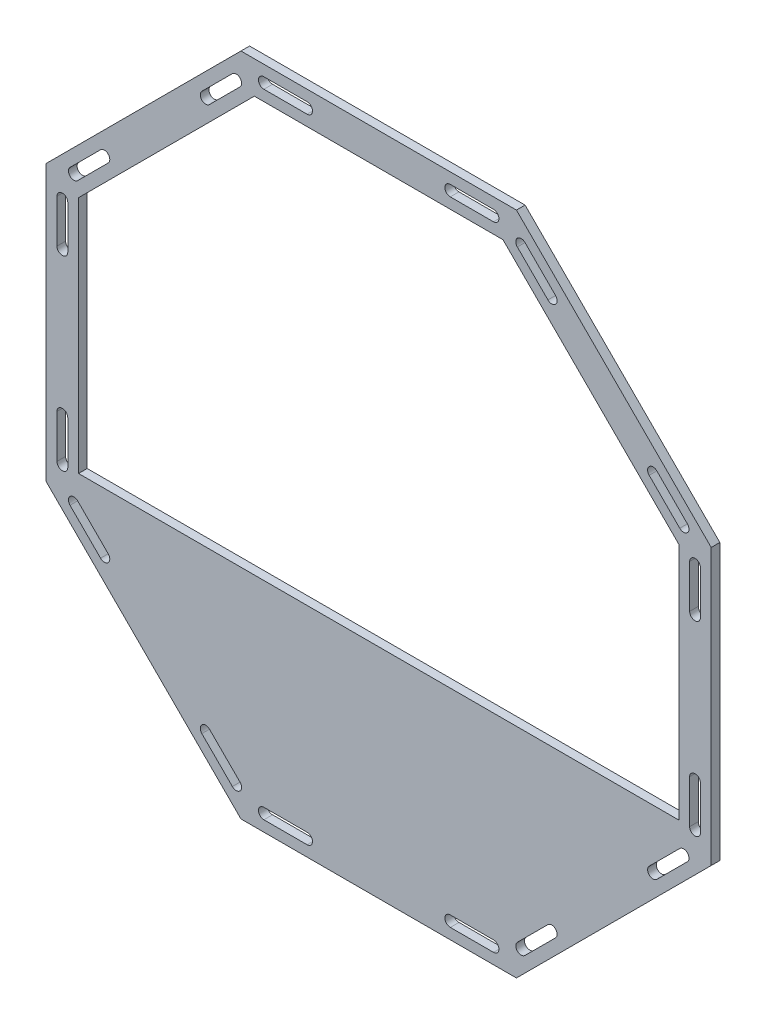
SolidWorks part; units mm, degrees
ref_plane "Front Plane" through (0, 0, 0) normal (0, 0, 1) x (1, 0, 0)
ref_plane "Top Plane" through (0, 0, 0) normal (0, 1, 0) x (1, 0, 0)
ref_plane "Right Plane" through (0, 0, 0) normal (1, 0, 0) x (0, 0, -1)
sketch "Sketch1" plane through (0, 0, 0) normal (0, 0, 1) x (1, 0, 0)
  line L1 (307.8122, -127.5) -> (307.8122, 127.5)
  line L2 (307.8122, 127.5) -> (127.5, 307.8122)
  line L3 (127.5, 307.8122) -> (-127.5, 307.8122)
  line L4 (-127.5, 307.8122) -> (-307.8122, 127.5)
  line L5 (-307.8122, 127.5) -> (-307.8122, -127.5)
  line L6 (-307.8122, -127.5) -> (-127.5, -307.8122)
  line L7 (-127.5, -307.8122) -> (127.5, -307.8122)
  line L8 (127.5, -307.8122) -> (307.8122, -127.5)
  circle A1 centre (0, 0) radius 333.1736 construction
  dimension "D1" = 255
extrude "Boss-Extrude1" add sketch "Sketch1" along normal blind 8
sketch "Sketch2" plane through (0, 0, 0) normal (0, 0, -1) x (-1, 0, 0)
  line L0 (-247.7082, 159.3198) -> (-261.8503, 173.4619)
  line L1 (-247.7082, 159.3198) -> (-159.3198, 247.7082)
  line L2 (-261.8503, 173.4619) -> (-173.4619, 261.8503)
  line L3 (-159.3198, 247.7082) -> (-173.4619, 261.8503)
  line L4 (-307.8122, 127.5) -> (-127.5, 307.8122) construction
  line L6 (-217.6561, 217.6561) -> (-147.1936, 147.1936) construction
  dimension "D1" = 20
  dimension "D2" = 125
  dimension "D3" = 62.5
sketch "Esquisse2" plane through (0, 0, 8) normal (0, 0, 1) x (1, 0, 0)
  line L0 (-277.8122, 115.0736) -> (-277.8122, -106.0285)
  line L1 (-127.5, 307.8122) -> (-307.8122, 127.5) construction
  line L2 (-307.8122, 127.5) -> (-307.8122, -127.5) construction
  line L5 (-115.0736, 277.8122) -> (-277.8122, 115.0736)
  line L13 (115.0736, 277.8122) -> (-115.0736, 277.8122)
  line L14 (-277.8122, -106.0285) -> (277.8122, -106.0285)
  line L25 (127.5, 307.8122) -> (-127.5, 307.8122) construction
  line L26 (0, 0) -> (0, 307.8122) construction
  line L30 (115.0736, 277.8122) -> (277.8122, 115.0736)
  line L31 (277.8122, 115.0736) -> (277.8122, -106.0285)
  dimension "D1" = 30
  dimension "D2" = 30
  dimension "D5" = 30
extrude "Enlèv. mat.-Extru.2" cut sketch "Esquisse2" against normal blind 10
sketch "Esquisse3" plane through (0, 0, 8) normal (0, 0, 1) x (1, 0, 0)
  line L0 (-282.1898, 131.8558) -> (-253.9055, 160.1401) construction
  line L3 (-285.7253, 135.3914) -> (-257.4411, 163.6757)
  line L4 (-278.6543, 128.3203) -> (-250.37, 156.6046)
  line L7 (-207.0337, 207.012) -> (-173.512, 173.4902) construction
  line L8 (-131.8776, 282.1681) -> (-160.1619, 253.8838) construction
  line L9 (-135.4131, 285.7036) -> (-163.6974, 257.4193)
  line L10 (-128.342, 278.6325) -> (-156.6263, 250.3483)
  line L13 (0.0158, 292.7747) -> (0.0158, -292.8498) construction
  line L16 (-292.7964, -0.0376) -> (292.828, -0.0376) construction
  line L17 (-121.271, 292.7747) -> (121.3026, -292.8498) construction
  line L20 (-106.271, 292.7747) -> (-66.271, 292.7747) construction
  line L23 (-106.271, 297.7747) -> (-66.271, 297.7747)
  line L24 (-106.271, 287.7747) -> (-66.271, 287.7747)
  line L25 (106.3026, 292.7747) -> (66.3026, 292.7747) construction
  line L28 (106.3026, 297.7747) -> (66.3026, 297.7747)
  line L31 (106.3026, 287.7747) -> (66.3026, 287.7747)
  line L34 (-292.7964, 121.2492) -> (292.828, -121.3243) construction
  line L37 (-292.7964, 106.2492) -> (-292.7964, 66.2492) construction
  line L40 (-297.7964, 106.2492) -> (-297.7964, 66.2492)
  line L43 (-287.7964, 106.2492) -> (-287.7964, 66.2492)
  line L46 (-292.7964, -106.3243) -> (-292.7964, -66.3243) construction
  line L49 (-297.7964, -106.3243) -> (-297.7964, -66.3243)
  line L50 (-287.7964, -106.3243) -> (-287.7964, -66.3243)
  line L53 (131.9092, 282.1681) -> (160.1935, 253.8838) construction
  line L56 (-292.7964, -121.3243) -> (292.828, 121.2492) construction
  line L57 (282.2214, -131.9309) -> (253.9372, -160.2152) construction
  line L58 (285.757, -135.4665) -> (257.4727, -163.7508)
  line L59 (278.6859, -128.3954) -> (250.4016, -156.6797)
  line L60 (131.9092, -282.2432) -> (160.1935, -253.9589) construction
  line L61 (135.4447, -285.7787) -> (163.729, -257.4944)
  line L62 (128.3737, -278.7076) -> (156.658, -250.4234)
  line L63 (106.3026, -292.8498) -> (66.3026, -292.8498) construction
  line L64 (106.3026, -297.8498) -> (66.3026, -297.8498)
  line L65 (106.3026, -287.8498) -> (66.3026, -287.8498)
  line L66 (-106.271, -292.8498) -> (-66.271, -292.8498) construction
  line L67 (-106.271, -297.8498) -> (-66.271, -297.8498)
  line L68 (-106.271, -287.8498) -> (-66.271, -287.8498)
  line L69 (-131.8776, -282.2432) -> (-160.1619, -253.9589) construction
  line L70 (-135.4131, -285.7787) -> (-163.6974, -257.4944)
  line L71 (-128.342, -278.7076) -> (-156.6263, -250.4234)
  line L72 (-282.1898, -131.9309) -> (-253.9055, -160.2152) construction
  line L73 (-285.7253, -135.4665) -> (-257.4411, -163.7508)
  line L74 (-278.6543, -128.3954) -> (-250.37, -156.6797)
  line L75 (292.828, -106.3243) -> (292.828, -66.3243) construction
  line L76 (297.828, -106.3243) -> (297.828, -66.3243)
  line L77 (287.828, -106.3243) -> (287.828, -66.3243)
  line L78 (292.828, 106.2492) -> (292.828, 66.2492) construction
  line L79 (297.828, 106.2492) -> (297.828, 66.2492)
  line L80 (287.828, 106.2492) -> (287.828, 66.2492)
  line L81 (127.5158, 307.7747) -> (-127.4842, -307.8498) construction
  line L82 (135.4447, 285.7036) -> (163.729, 257.4193)
  line L83 (128.3737, 278.6325) -> (156.658, 250.3483)
  line L84 (282.2214, 131.8558) -> (253.9372, 160.1401) construction
  line L85 (285.757, 135.3914) -> (257.4727, 163.6757)
  line L86 (278.6859, 128.3203) -> (250.4016, 156.6046)
  arc A32 (135.4447, 285.7036) -> (128.3737, 278.6325) centre (131.9092, 282.1681) ccw
  arc A33 (-285.7253, 135.3914) -> (-278.6543, 128.3203) centre (-282.1898, 131.8558) ccw
  arc A34 (-250.37, 156.6046) -> (-257.4411, 163.6757) centre (-253.9055, 160.1401) ccw
  arc A35 (-135.4131, 285.7036) -> (-128.342, 278.6325) centre (-131.8776, 282.1681) cw
  arc A36 (-156.6263, 250.3483) -> (-163.6974, 257.4193) centre (-160.1619, 253.8838) cw
  arc A37 (-106.271, 297.7747) -> (-106.271, 287.7747) centre (-106.271, 292.7747) ccw
  arc A38 (-66.271, 287.7747) -> (-66.271, 297.7747) centre (-66.271, 292.7747) ccw
  arc A39 (106.3026, 297.7747) -> (106.3026, 287.7747) centre (106.3026, 292.7747) cw
  arc A40 (66.3026, 287.7747) -> (66.3026, 297.7747) centre (66.3026, 292.7747) cw
  arc A41 (-297.7964, 106.2492) -> (-287.7964, 106.2492) centre (-292.7964, 106.2492) cw
  arc A42 (-287.7964, 66.2492) -> (-297.7964, 66.2492) centre (-292.7964, 66.2492) cw
  arc A43 (-297.7964, -106.3243) -> (-287.7964, -106.3243) centre (-292.7964, -106.3243) ccw
  arc A44 (-287.7964, -66.3243) -> (-297.7964, -66.3243) centre (-292.7964, -66.3243) ccw
  arc A45 (285.757, -135.4665) -> (278.6859, -128.3954) centre (282.2214, -131.9309) ccw
  arc A46 (250.4016, -156.6797) -> (257.4727, -163.7508) centre (253.9372, -160.2152) ccw
  arc A47 (135.4447, -285.7787) -> (128.3737, -278.7076) centre (131.9092, -282.2432) cw
  arc A48 (156.658, -250.4234) -> (163.729, -257.4944) centre (160.1935, -253.9589) cw
  arc A49 (106.3026, -297.8498) -> (106.3026, -287.8498) centre (106.3026, -292.8498) ccw
  arc A50 (66.3026, -287.8498) -> (66.3026, -297.8498) centre (66.3026, -292.8498) ccw
  arc A51 (-106.271, -297.8498) -> (-106.271, -287.8498) centre (-106.271, -292.8498) cw
  arc A52 (-66.271, -287.8498) -> (-66.271, -297.8498) centre (-66.271, -292.8498) cw
  arc A53 (-135.4131, -285.7787) -> (-128.342, -278.7076) centre (-131.8776, -282.2432) ccw
  arc A54 (-156.6263, -250.4234) -> (-163.6974, -257.4944) centre (-160.1619, -253.9589) ccw
  arc A55 (-285.7253, -135.4665) -> (-278.6543, -128.3954) centre (-282.1898, -131.9309) cw
  arc A56 (-250.37, -156.6797) -> (-257.4411, -163.7508) centre (-253.9055, -160.2152) cw
  arc A57 (297.828, -106.3243) -> (287.828, -106.3243) centre (292.828, -106.3243) cw
  arc A58 (287.828, -66.3243) -> (297.828, -66.3243) centre (292.828, -66.3243) cw
  arc A59 (297.828, 106.2492) -> (287.828, 106.2492) centre (292.828, 106.2492) ccw
  arc A60 (287.828, 66.2492) -> (297.828, 66.2492) centre (292.828, 66.2492) ccw
  arc A61 (156.658, 250.3483) -> (163.729, 257.4193) centre (160.1935, 253.8838) ccw
  arc A62 (285.757, 135.3914) -> (278.6859, 128.3203) centre (282.2214, 131.8558) cw
  arc A63 (250.4016, 156.6046) -> (257.4727, 163.6757) centre (253.9372, 160.1401) cw
  point P10 (146.0513, 268.0259)
  point P14 (-268.0477, 145.998)
  point P23 (-146.0197, 268.0259)
  point P34 (-86.271, 292.7747)
  point P41 (86.3026, 292.7747)
  point P48 (-292.7964, 86.2492)
  point P55 (-292.7964, -86.3243)
  point P64 (268.0793, -146.0731)
  point P71 (146.0513, -268.101)
  point P78 (86.3026, -292.8498)
  point P85 (-86.271, -292.8498)
  point P92 (-146.0197, -268.101)
  point P99 (-268.0477, -146.0731)
  point P106 (292.828, -86.3243)
  point P113 (292.828, 86.2492)
  point P121 (268.0793, 145.998)
  dimension "D1" = 5
  dimension "D2" = 15
  dimension "D3" = 40
extrude "Enlèv. mat.-Extru.3" cut sketch "Esquisse3" against normal blind 10
